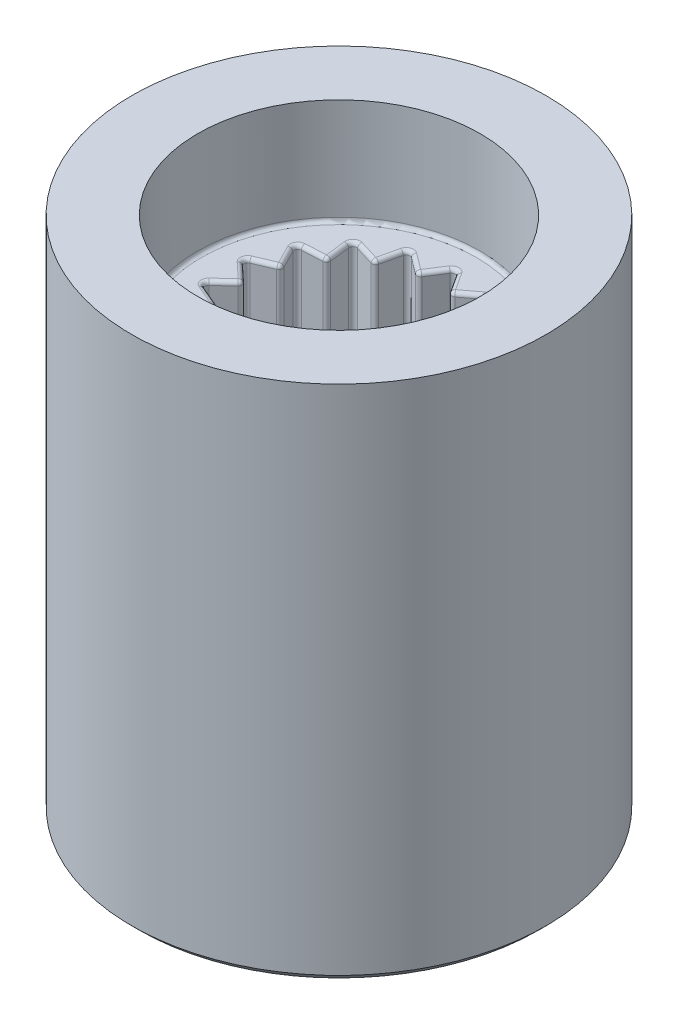
SolidWorks part; units mm, degrees
ref_plane "前视基准面" through (0, 0, 0) normal (0, 0, 1) x (1, 0, 0)
ref_plane "上视基准面" through (0, 0, 0) normal (0, 1, 0) x (1, 0, 0)
ref_plane "右视基准面" through (0, 0, 0) normal (1, 0, 0) x (0, 0, -1)
sketch "Sketch2" plane through (0, 0, 0) normal (0, 1, 0) x (1, 0, 0)
  circle A0 centre (0, 0) radius 5.5
  circle A1 centre (0, 0) radius 3.75
extrude "Boss-Extrude1" add sketch "Sketch2" along normal blind 13.7
sketch "Sketch3" plane through (0, 0, 0) normal (0, 1, 0) x (1, 0, 0)
  line L0 (0, 0) -> (0, 3.1672) construction
  line L1 (0, 0) -> (0.5965, 3.3826) construction
  line L2 (1.0833, 2.9762) -> (0, 0) construction
  line L3 (0, 3.1672) -> (0.4391, 2.4901)
  line L4 (1.0833, 2.9762) -> (0.4391, 2.4901)
  line L5 (1.0833, 2.9762) -> (1.2643, 2.1898)
  line L6 (2.0359, 2.4262) -> (1.2643, 2.1898)
  line L7 (2.0359, 2.4262) -> (1.937, 1.6253)
  line L8 (2.7429, 1.5836) -> (1.937, 1.6253)
  line L9 (2.7429, 1.5836) -> (2.3761, 0.8648)
  line L10 (3.1191, 0.55) -> (2.3761, 0.8648)
  line L11 (3.1191, 0.55) -> (2.5286, 0)
  line L12 (3.1191, -0.55) -> (2.5286, 0)
  line L13 (3.1191, -0.55) -> (2.3761, -0.8648)
  line L14 (2.7429, -1.5836) -> (2.3761, -0.8648)
  line L15 (2.7429, -1.5836) -> (1.937, -1.6253)
  line L16 (2.0359, -2.4262) -> (1.937, -1.6253)
  line L17 (2.0359, -2.4262) -> (1.2643, -2.1898)
  line L18 (1.0833, -2.9762) -> (1.2643, -2.1898)
  line L19 (1.0833, -2.9762) -> (0.4391, -2.4901)
  line L20 (0, -3.1672) -> (0.4391, -2.4901)
  line L21 (0, -3.1672) -> (-0.4391, -2.4901)
  line L22 (-1.0833, -2.9762) -> (-0.4391, -2.4901)
  line L23 (-1.0833, -2.9762) -> (-1.2643, -2.1898)
  line L24 (-2.0359, -2.4262) -> (-1.2643, -2.1898)
  line L25 (-2.0359, -2.4262) -> (-1.937, -1.6253)
  line L26 (-2.7429, -1.5836) -> (-1.937, -1.6253)
  line L27 (-2.7429, -1.5836) -> (-2.3761, -0.8648)
  line L28 (-3.1191, -0.55) -> (-2.3761, -0.8648)
  line L29 (-3.1191, -0.55) -> (-2.5286, 0)
  line L30 (-3.1191, 0.55) -> (-2.5286, 0)
  line L31 (-3.1191, 0.55) -> (-2.3761, 0.8648)
  line L32 (-2.7429, 1.5836) -> (-2.3761, 0.8648)
  line L33 (-2.7429, 1.5836) -> (-1.937, 1.6253)
  line L34 (-2.0359, 2.4262) -> (-1.937, 1.6253)
  line L35 (-2.0359, 2.4262) -> (-1.2643, 2.1898)
  line L36 (-1.0833, 2.9762) -> (-1.2643, 2.1898)
  line L37 (-1.0833, 2.9762) -> (-0.4391, 2.4901)
  line L38 (0, 3.1672) -> (-0.4391, 2.4901)
  circle A0 centre (0, 0) radius 4.6077
  circle A2 centre (0, 0) radius 2.6 construction
  point P8 (0, 0)
  point P12 (0, 0)
  point P15 (0, 0)
  point P18 (0, 0)
  point P21 (0, 0)
  point P24 (0, 0)
  point P27 (0, 0)
  point P30 (0, 0)
  point P33 (0, 0)
  point P36 (0, 0)
  point P39 (0, 0)
  point P42 (0, 0)
  point P45 (0, 0)
  point P48 (0, 0)
  point P51 (0, 0)
  point P54 (0, 0)
  point P57 (0, 0)
  point P60 (0, 0)
  point P61 (0, 0)
extrude "Boss-Extrude2" add sketch "Sketch3" along normal offset from surface (10.9 mm away) 2.8 up to face at (0, 13.7, 5.5)
fillet "Fillet1" radius 0.1 75 edges at (1.9864, 0, -2.0258) (1.6501, 0, -2.308) (1.2643, 5.45, -2.1898) (2.0359, 5.45, -2.4262) (0, 10.9, 3.75) (0.2195, 10.9, -2.8287) (-0.2195, 10.9, -2.8287) (-0.7612, 10.9, -2.7332) (-1.1738, 10.9, -2.583) (-1.6501, 10.9, -2.308) (-1.9864, 10.9, -2.0258) (-2.3399, 10.9, -1.6045) (-2.5595, 10.9, -1.2242) (-2.7476, 10.9, -0.7074) (-2.8238, 10.9, -0.275) (-2.8238, 10.9, 0.275) (-2.7476, 10.9, 0.7074) (-2.5595, 10.9, 1.2242) (-2.3399, 10.9, 1.6045) (-1.9864, 10.9, 2.0258) (-1.6501, 10.9, 2.308) (-1.1738, 10.9, 2.583) (-0.7612, 10.9, 2.7332) (-0.2195, 10.9, 2.8287) (0.2195, 10.9, 2.8287) (0.7612, 10.9, 2.7332) (1.1738, 10.9, 2.583) (1.6501, 10.9, 2.308) (1.9864, 10.9, 2.0258) (2.3399, 10.9, 1.6045) (2.5595, 10.9, 1.2242) (2.7476, 10.9, 0.7074) (2.8238, 10.9, 0.275) (2.8238, 10.9, -0.275) (2.7476, 10.9, -0.7074) (2.5595, 10.9, -1.2242) (2.3399, 10.9, -1.6045) (1.9864, 10.9, -2.0258) (1.6501, 10.9, -2.308) (1.1738, 10.9, -2.583) (0.7612, 10.9, -2.7332) (-2.3761, 5.45, -0.8648) (-3.1191, 5.45, -0.55) (-2.5286, 5.45, 0) (-3.1191, 5.45, 0.55) (-2.3761, 5.45, 0.8648) (-2.7429, 5.45, 1.5836) (-1.937, 5.45, 1.6253) (-2.0359, 5.45, 2.4262) (-1.0833, 5.45, 2.9762) (-1.2643, 5.45, 2.1898) (-0.4391, 5.45, 2.4901) (0, 5.45, 3.1672) (0.4391, 5.45, 2.4901) (1.0833, 5.45, 2.9762) (2.0359, 5.45, 2.4262) (1.2643, 5.45, 2.1898) (2.7429, 5.45, 1.5836) (1.937, 5.45, 1.6253) (2.3761, 5.45, 0.8648) (3.1191, 5.45, 0.55) (2.5286, 5.45, 0) (3.1191, 5.45, -0.55) (2.7429, 5.45, -1.5836) (2.3761, 5.45, -0.8648) (1.937, 5.45, -1.6253) (1.0833, 5.45, -2.9762) (0.4391, 5.45, -2.4901) (0, 5.45, -3.1672) (-0.4391, 5.45, -2.4901) (-1.0833, 5.45, -2.9762) (-1.2643, 5.45, -2.1898) (-2.0359, 5.45, -2.4262) (-1.937, 5.45, -1.6253) (-2.7429, 5.45, -1.5836)
sketch "草图1" plane through (0, 0, 0) normal (0, -1, 0) x (1, 0, 0)
  circle A0 centre (0, 0) radius 5.5
extrude "凸台-拉伸1" add sketch "草图1" along normal blind 0.1
chamfer "倒角1" distance 0.2 angle 45 1 edges at (0, -0.1, -5.5)
